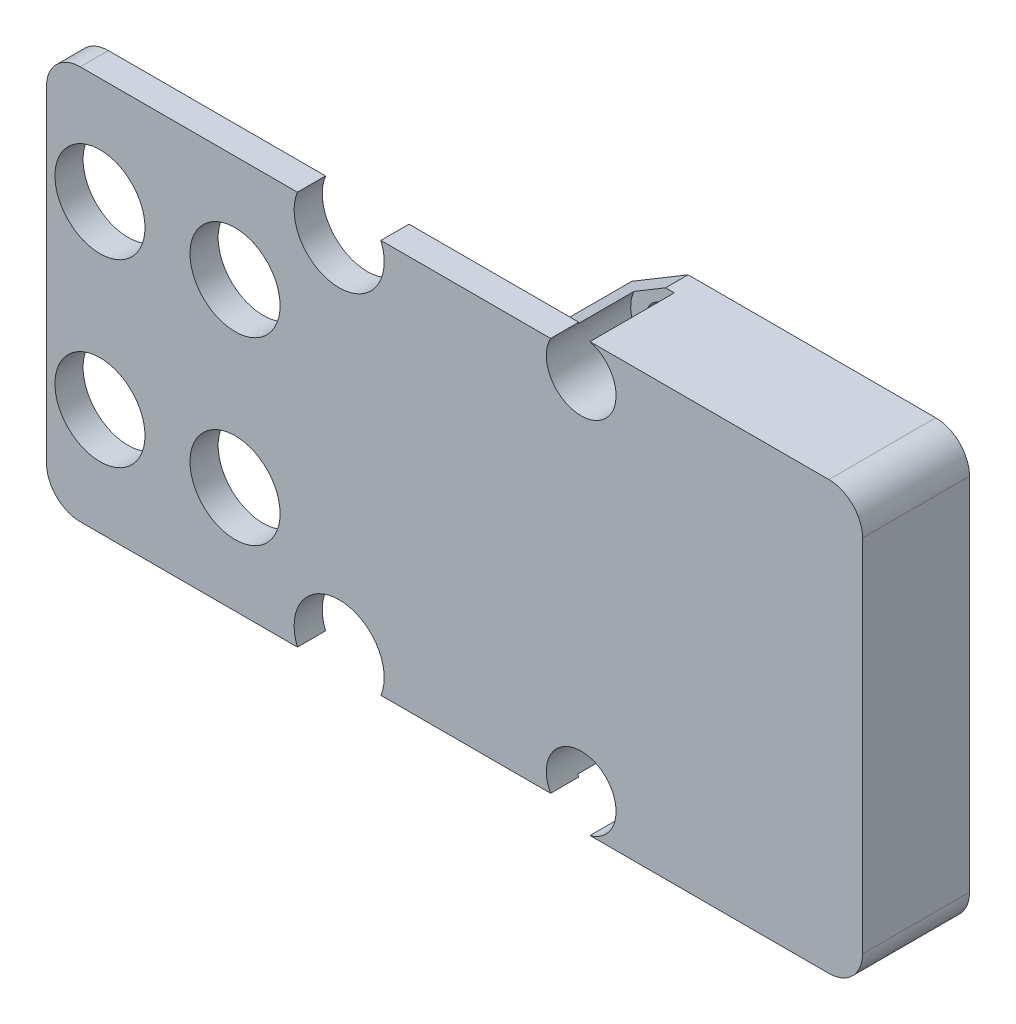
SolidWorks part; units mm, degrees
ref_plane "Alzado" through (0, 0, 0) normal (0, 0, 1) x (1, 0, 0)
ref_plane "Planta" through (0, 0, 0) normal (0, 1, 0) x (1, 0, 0)
ref_plane "Vista lateral" through (0, 0, 0) normal (1, 0, 0) x (0, 0, -1)
sketch "Croquis1" plane through (0, 0, 0) normal (0, 0, 1) x (1, 0, 0)
  line L0 (-69.5865, 30.6996) -> (-44.5865, 30.6996)
  line L1 (-69.5865, -7.3004) -> (-44.5865, -7.3004)
  line L2 (-44.5865, 30.6996) -> (-44.5865, -7.3004)
  line L3 (-69.5865, 27.6996) -> (-74.5865, 27.6996) construction
  line L4 (-74.5865, 27.6996) -> (-74.5865, -4.3004)
  line L5 (-74.5865, -4.3004) -> (-69.5865, -7.3004)
  line L6 (-74.5865, 27.6996) -> (-69.5865, 30.6996)
  circle A0 centre (-69.5865, 27.6996) radius 1.7074
  circle A1 centre (-69.5865, -4.3004) radius 1.7074
  dimension "D1" = 32
  dimension "D2" = 3
  dimension "D3" = 3
  dimension "D4" = 25
  dimension "D5" = 25
extrude "Saliente-Extruir1" add sketch "Croquis1" along normal blind 9.5
sketch "Croquis4" plane through (0, 0, 9.5) normal (0, 0, 1) x (1, 0, 0)
  line L0 (-72.0865, 29.1996) -> (-117.0865, 29.1996)
  line L1 (-69.5865, 30.6996) -> (-74.5865, 27.6996) construction
  line L2 (-117.0865, 29.1996) -> (-117.0865, -5.8004)
  line L3 (-117.0865, -5.8004) -> (-72.0865, -5.8004)
  line L4 (-74.5865, -4.3004) -> (-69.5865, -7.3004) construction
  line L5 (-72.0865, -5.8004) -> (-74.5865, -4.3004)
  line L6 (-74.5865, -4.3004) -> (-74.5865, 27.6996)
  line L7 (-74.5865, 27.6996) -> (-72.0865, 29.1996)
  dimension "D1" = 45
extrude "Saliente-Extruir2" add sketch "Croquis4" against normal blind 2.5
sketch "Croquis5" plane through (0, 0, 9.5) normal (0, 0, 1) x (1, 0, 0)
  line L0 (-69.5865, -4.3004) -> (-117.0865, -4.3004) construction
  line L1 (-117.0865, 29.1996) -> (-117.0865, -5.8004) construction
  line L2 (-69.5865, 27.6996) -> (-117.0865, 27.6996) construction
  line L3 (-121.5865, -4.3004) -> (-91.0865, 27.6996) construction
  line L4 (-91.0865, 27.6996) -> (-121.5865, 27.6996) construction
  line L5 (-121.5865, 27.6996) -> (-91.0865, -4.3004) construction
  line L11 (-112.3365, 19.6996) -> (-100.3365, 3.6996) construction
  line L12 (-112.3365, 3.6996) -> (-100.3365, 19.6996) construction
  circle A0 centre (-91.0865, -4.3004) radius 4
  circle A1 centre (-91.0865, 27.6996) radius 4
  circle A2 centre (-121.5865, -4.3004) radius 3.5
  circle A3 centre (-121.5865, 27.6996) radius 3.5
  circle A4 centre (-100.3365, 19.6996) radius 4
  circle A5 centre (-112.3365, 19.6996) radius 4
  circle A6 centre (-112.3365, 3.6996) radius 4
  circle A7 centre (-100.3365, 3.6996) radius 4
  point P16 (-106.3365, 11.6996)
  dimension "D1" = 21.5
  dimension "D2" = 30.5
  dimension "D3" = 16
  dimension "D5" = 7
  dimension "D6" = 8
  dimension "D7" = 7
  dimension "D8" = 8
  dimension "D9" = 8
  dimension "D10" = 8
  dimension "D11" = 8
  dimension "D12" = 8
  dimension "D4" = 12
extrude "Cortar-Extruir1" cut sketch "Croquis5" against normal up to vertex (2.5 mm away)
fillet "Redondeo1" radius 3 4 edges at (-117.0865, 29.1996, 8.25) (-117.0865, -5.8004, 8.25) (-44.5865, 30.6996, 4.75) (-44.5865, -7.3004, 4.75)
sketch "Croquis6" plane through (0, 0, 9.5) normal (0, 0, 1) x (1, 0, 0)
  circle A0 centre (-69.5865, 27.6996) radius 3.1
  circle A1 centre (-69.5865, -4.3004) radius 3.1
  dimension "D1" = 6.2
  dimension "D2" = 6.2
extrude "Cortar-Extruir2" cut sketch "Croquis6" against normal blind 7.5
